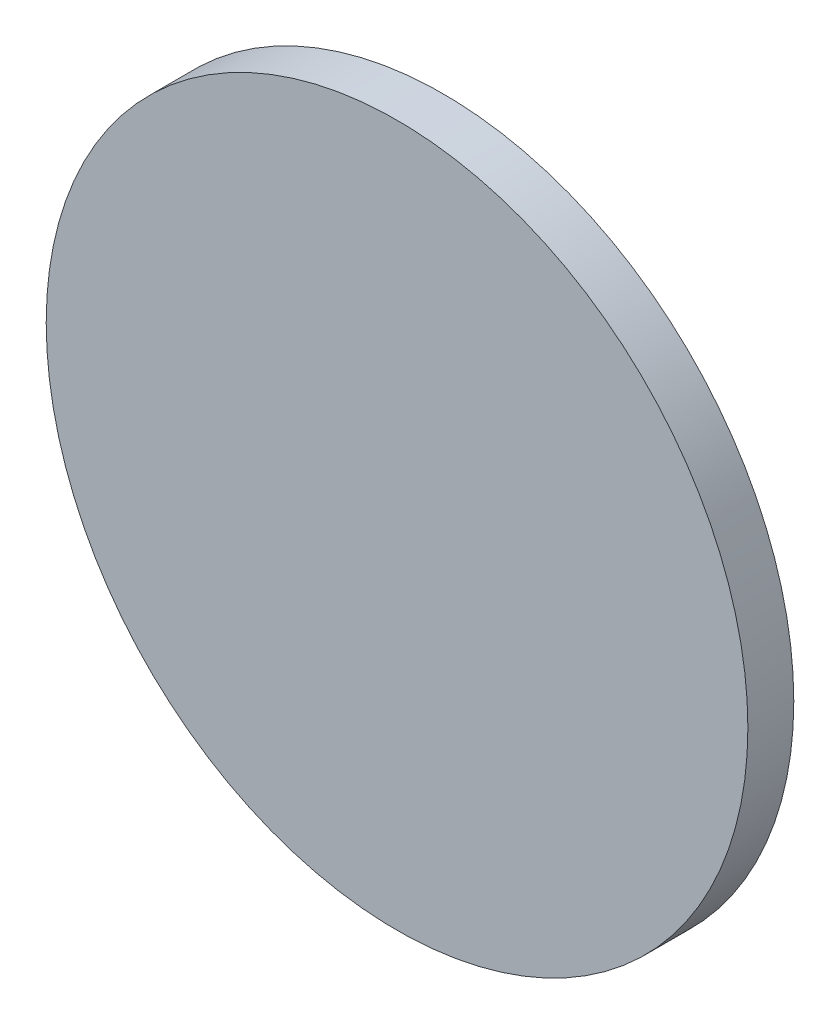
SolidWorks part; units mm, degrees
ref_plane "Front Plane" through (0, 0, 0) normal (0, 0, 1) x (1, 0, 0)
ref_plane "Top Plane" through (0, 0, 0) normal (0, 1, 0) x (1, 0, 0)
ref_plane "Right Plane" through (0, 0, 0) normal (1, 0, 0) x (0, 0, -1)
sketch "Sketch1" plane through (0, 0, 0) normal (0, 0, 1) x (1, 0, 0)
  circle A0 centre (0, 0) radius 76.397
extrude "Boss-Extrude1" add sketch "Sketch1" along normal blind 10
